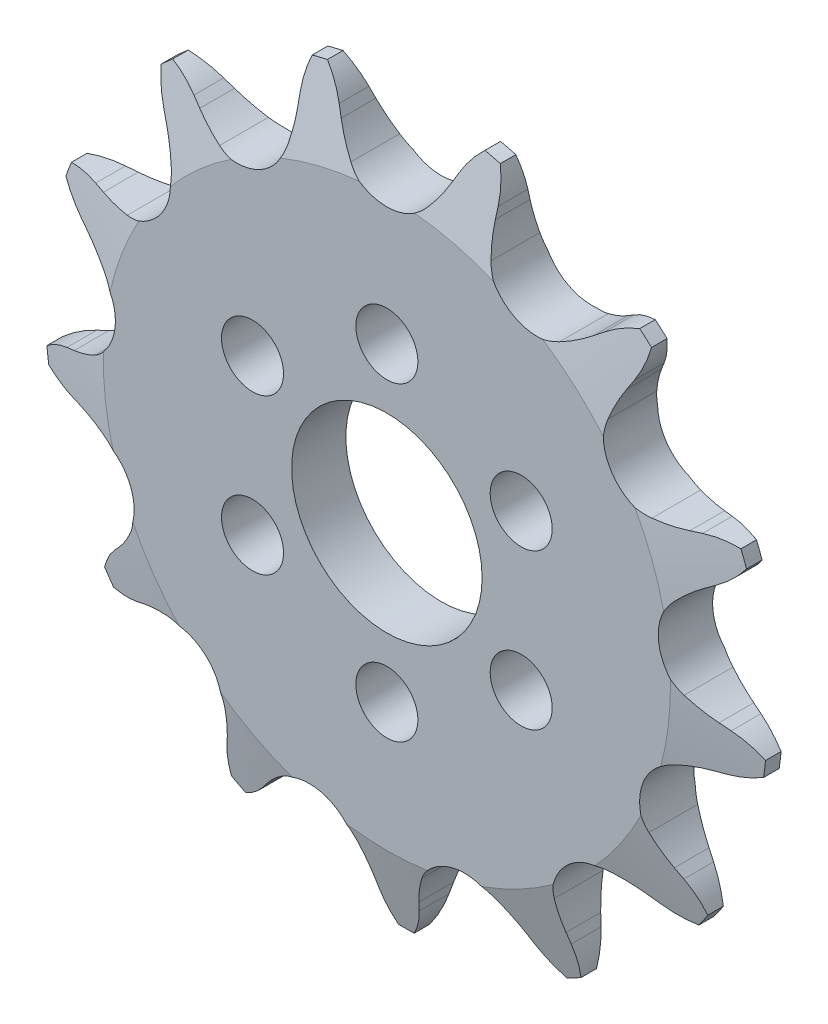
SolidWorks part; units mm, degrees
material "AISI 4130 Steel, annealed at 865C"
ref_plane "Front Plane" through (0, 0, 0) normal (0, 0, 1) x (1, 0, 0)
ref_plane "Top Plane" through (0, 0, 0) normal (0, 1, 0) x (1, 0, 0)
ref_plane "Right Plane" through (0, 0, 0) normal (1, 0, 0) x (0, 0, -1)
sketch "Sketch0" plane through (0, 0, 0) normal (0, 0, 1) x (1, 0, 0)
  line L0 (7.9375, -32.2037) -> (0, 0) construction
  line L1 (0, 0) -> (21.9941, -24.8262) construction
  line L2 (0, 0) -> (-7.9375, -32.2037) construction
  line L3 (7.9375, -32.2037) -> (21.9941, -24.8262) construction
  line L4 (7.9375, -32.2037) -> (-7.9375, -32.2037) construction
  line L5 (13.9722, -31.0531) -> (13.2992, -30.2445)
  line L6 (7.9375, -32.2037) -> (0, -34.1601) construction
  line L7 (2.0593, -33.9894) -> (2.2794, -32.9606)
  line L8 (0, -32.2037) -> (0, -36.9662) construction
  line L9 (10.9997, -28.0711) -> (3.0984, -38.7342) construction
  line L10 (0, 0) -> (0, -32.2037) construction
  line L11 (13.2992, -30.2445) -> (3.0984, -38.7342) construction
  line L12 (0, -36.9662) -> (0, -37.9761) construction
  line L13 (20.5322, -25.5935) -> (13.9722, -31.0531) construction
  circle A0 centre (0, 0) radius 36.9662 construction
  circle A1 centre (0, 0) radius 33.1675 construction
  arc A2 (-7.9217, -40.5803) -> (25.8729, -32.2507) centre (0, 0) ccw
  circle A3 centre (0, 0) radius 37.9761 construction
  circle A4 centre (7.9375, -32.2037) radius 5.08 construction
  arc A7 (10.9997, -28.0711) -> (3.3055, -29.9676) centre (7.9375, -32.2037) ccw
  circle A8 centre (7.9375, -32.2037) radius 5.1435 construction
  arc A9 (13.9722, -31.0531) -> (25.8729, -32.2507) centre (20.5322, -25.5935) ccw
  arc A10 (13.2992, -30.2445) -> (10.9997, -28.0711) centre (3.0984, -38.7342) ccw
  arc A11 (2.0593, -33.9894) -> (-7.9217, -40.5803) centre (-6.2865, -32.2037) cw
  arc A12 (2.2794, -32.9606) -> (3.3055, -29.9676) centre (15.2572, -35.7373) cw
  dimension "D1" = 5.1435
  dimension "R" = 5.1435
sketch "Sketch1" plane through (0, 0, 0) normal (1, 0, 0) x (0, 0, -1)
  line L0 (2.7781, 0) -> (-2.7781, 0)
  line L1 (-2.7781, 0) -> (-2.7781, 29.0287)
  line L2 (-2.7781, 29.0287) -> (-0.7937, 36.9662)
  line L3 (-0.7937, 36.9662) -> (0.7937, 36.9662)
  line L4 (0.7937, 36.9662) -> (2.7781, 29.0287)
  line L5 (2.7781, 29.0287) -> (2.7781, 0)
  line L7 (0, 36.9662) -> (0, 0) construction
  line L8 (-2.7781, 29.0287) -> (2.7781, 29.0287) construction
  line L9 (0, 36.9662) -> (0, -36.9662) construction
  line L10 (-2.7781, 29.0287) -> (-2.7781, 36.9662) construction
  line L11 (-2.7781, 36.9662) -> (-0.7937, 36.9662) construction
  line L12 (0.7937, 36.9662) -> (2.7781, 36.9662) construction
  line L13 (2.7781, 36.9662) -> (2.7781, 29.0287) construction
revolve "Revolve1" add sketch "Sketch1" angle 360 mid plane about L0
extrude "Cut-Extrude1" cut sketch "Sketch0" against normal through all and the other way through all
pattern_circular "CirPattern1" count 13 over 360 about axis through (0, 0, 0) along (0, 0, 1) of "Cut-Extrude1"
sketch "Sketch2" plane through (0, 0, 0) normal (0, 0, 1) x (1, 0, 0)
  circle A0 centre (0, 0) radius 7.9375 construction
  circle A1 centre (0, 0) radius 30.1625
  circle A2 centre (0, 0) radius 36.957 construction
  dimension "Bore" = 15.875
  dimension "Hub Dia." = 60.325
  dimension "OD" = 73.914
sketch "Sketch3" plane through (0, 0, 0) normal (0, 0, 1) x (1, 0, 0)
  circle A1 centre (0, 0) radius 9.75
  circle A2 centre (0, 0) radius 36.957 construction
  circle A3 centre (0, 0) radius 36.957
extrude "Cut-Extrude2" cut sketch "Sketch3" along normal through all and the other way through all flip side to cut
sketch "Sketch4" plane through (0, 0, -2.7781) normal (0, 0, -1) x (-1, 0, 0)
  line L0 (0, 0) -> (0, 15.875) construction
  circle A0 centre (0, 15.875) radius 3.175
  circle A1 centre (13.7482, 7.9375) radius 3.175
  circle A2 centre (13.7482, -7.9375) radius 3.175
  circle A3 centre (0, -15.875) radius 3.175
  circle A4 centre (-13.7482, -7.9375) radius 3.175
  circle A5 centre (-13.7482, 7.9375) radius 3.175
  point P17 (0, 0)
  dimension "D1" = 6
extrude "Cut-Extrude3" cut sketch "Sketch4" against normal through all
sketch "Sketch5" plane through (0, 0, 2.7781) normal (0, 0, 1) x (1, 0, 0)
  line L0 (0, 0) -> (9.75, 0) construction
  line L1 (9.75, 0) -> (11, 0) construction
  circle A0 centre (0, 0) radius 11 construction
  circle A1 centre (0, 0) radius 9.75 construction
sketch "Sketch6" plane through (0, 0, -2.7781) normal (0, 0, -1) x (-1, 0, 0)
  circle A0 centre (0, 0) radius 28.024 construction
  circle A1 centre (0, 0) radius 24.2521 construction
ref_plane "Plane1" through (-29.6833, 20.4889, 0) normal (-0.823, 0.5681, 0) x (0, 0, 1)
ref_plane "Plane2" through (-35.8049, 4.3475, 0) normal (-0.9927, 0.1205, 0) x (0, 0, 1)
ref_plane "Plane3" through (-33.724, -12.7898, 0) normal (-0.935, -0.3546, 0) x (0, 0, 1)
ref_plane "Plane4" through (-23.9174, -26.9972, 0) normal (-0.6631, -0.7485, 0) x (-0.7485, 0.6631, 0)
ref_plane "Plane5" through (-8.6316, -35.0198, 0) normal (-0.2393, -0.9709, 0) x (-0.9709, 0.2393, 0)
sketch "Sketch7" plane through (-29.6833, 20.4889, 0) normal (-0.823, 0.5681, 0) x (0, 0, 1)
  line L0 (-6.5106, 0) -> (7.7601, 0)
sketch "Sketch8" plane through (-35.8049, 4.3475, 0) normal (-0.9927, 0.1205, 0) x (0, 0, 1)
  line L0 (-7.786, 0) -> (10.2102, 0)
sketch "Sketch9" plane through (-33.724, -12.7898, 0) normal (-0.935, -0.3546, 0) x (0, 0, 1)
  line L0 (-7.6671, 0) -> (14.0341, 0)
  line L1 (-2.7781, 0) -> (2.7781, 0) construction
sketch "Sketch10" plane through (-23.9174, -26.9972, 0) normal (-0.6631, -0.7485, 0) x (-0.7485, 0.6631, 0)
  line L0 (0, -3.5829) -> (0, 5.4944)
sketch "Sketch11" plane through (-8.6316, -35.0198, 0) normal (-0.2393, -0.9709, 0) x (-0.9709, 0.2393, 0)
  line L0 (0, -5.4358) -> (0, 8.5188)
split line "Split Line7"
split line "Split Line8"
split line "Split Line9"
split line "Split Line10"
split line "Split Line11"
equation "\"360/N@Sketch0\" = 360/\"Teeth@CirPattern1\""
equation "\"Ds@Sketch0\" = 1.005 * \"Dr@Sketch0\" + 0.003"
equation "\"R@Sketch0\" = 1/2 * \"Ds@Sketch0\""
equation "\"A@Sketch0\" = 35 +  ( 60 / \"Teeth@CirPattern1\" ) "
equation "\"B@Sketch0\" = 18 -  ( 56 / \"Teeth@CirPattern1\" )"
equation "\"ac@Sketch0\" = 0.8 * \"Dr@Sketch0\""
equation "\"ab@Sketch0\" = 1.4 * \"Dr@Sketch0\""
equation "\"J@Sketch0\" = 0.3 * \"Pitch@Sketch0\""
equation "\"h@Sketch1\" = \"Pitch@Sketch0\" / 2"
equation "\"g@Sketch1\" = \"h@Sketch1\" / 4"
